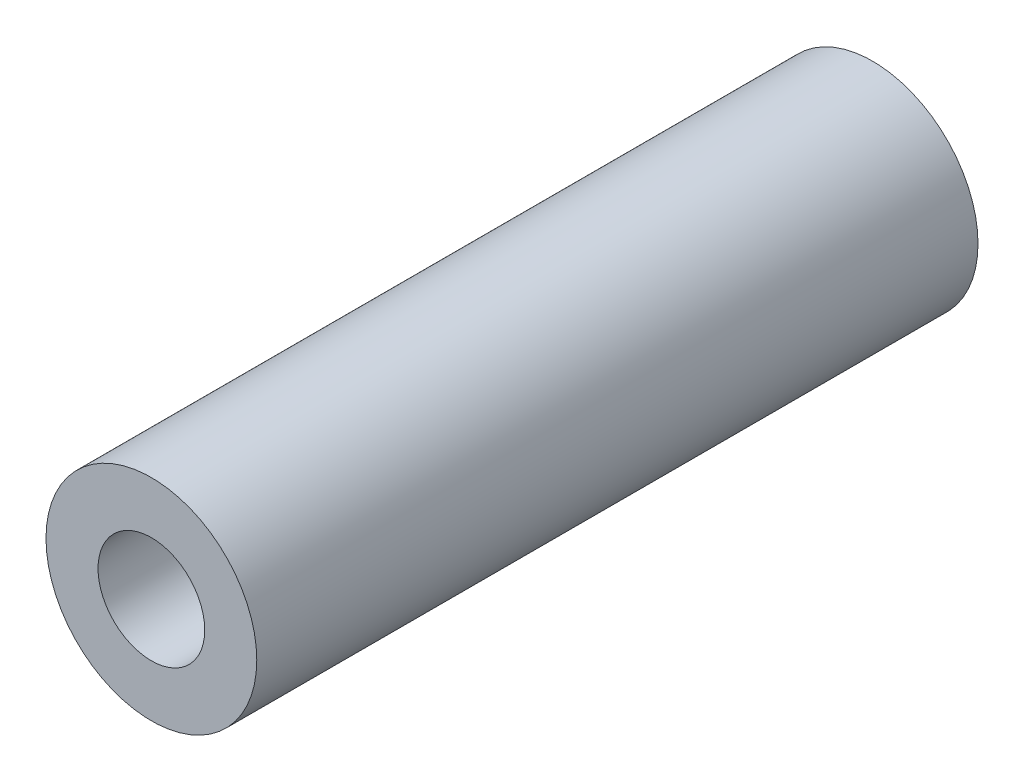
SolidWorks part; units mm, degrees
ref_plane "Front Plane" through (0, 0, 0) normal (0, 0, 1) x (1, 0, 0)
ref_plane "Top Plane" through (0, 0, 0) normal (0, 1, 0) x (1, 0, 0)
ref_plane "Right Plane" through (0, 0, 0) normal (1, 0, 0) x (0, 0, -1)
sketch "S01 - Solid post blank - 16 mm" plane through (0, 0, 0) normal (0, 0, 1) x (1, 0, 0)
  circle A0 centre (0, 0) radius 8
extrude "01 - Solid post blank - 16 mm" add sketch "S01 - Solid post blank - 16 mm" along normal blind 54.75 from offset 1.5
sketch "S02 - Rear M6 heat-set insert seat" plane through (0, 0, 0) normal (0, 0, 1) x (1, 0, 0)
  circle A0 centre (0, 0) radius 4.05
extrude "02 - Rear M6 heat-set insert seat" cut sketch "S02 - Rear M6 heat-set insert seat" along normal blind 14.35 from offset 1.6 offset against normal yes
sketch "S03 - Front M6 heat-set insert seat" plane through (0, 0, 0) normal (0, 0, 1) x (1, 0, 0)
  circle A0 centre (0, 0) radius 4.05
extrude "03 - Front M6 heat-set insert seat" cut sketch "S03 - Front M6 heat-set insert seat" along normal blind 14.35 from offset 39
